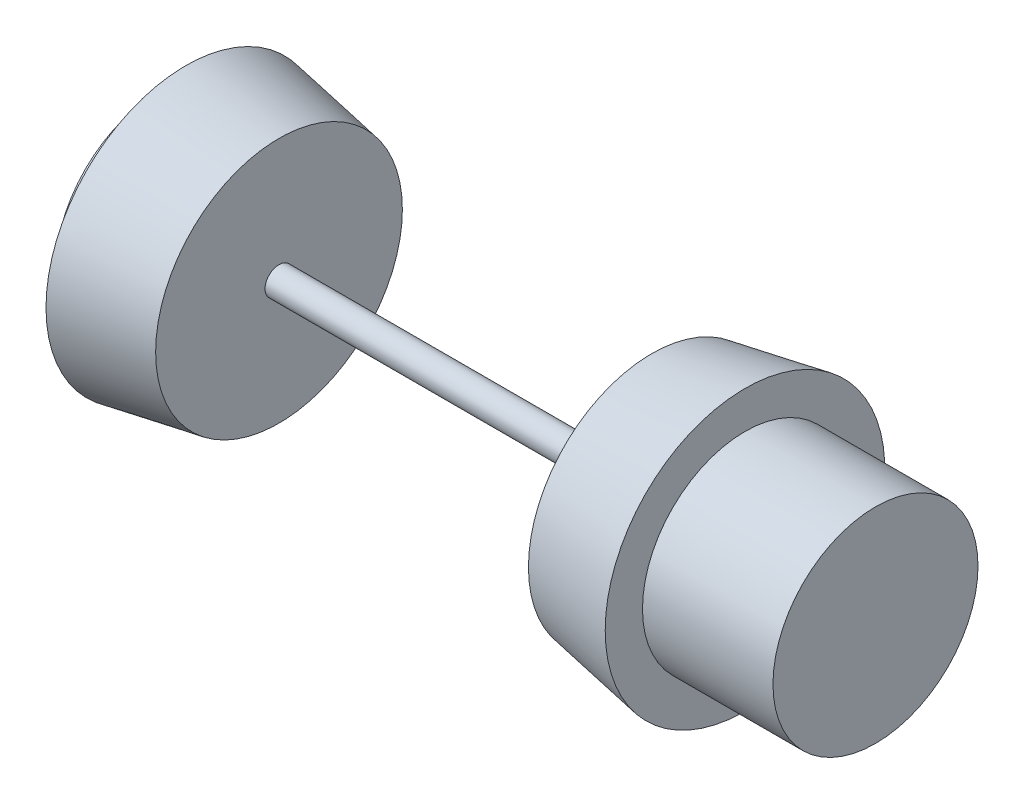
SolidWorks part; units mm, degrees
ref_plane "Front Plane" through (0, 0, 0) normal (0, 0, 1) x (1, 0, 0)
ref_plane "Top Plane" through (0, 0, 0) normal (0, 1, 0) x (1, 0, 0)
ref_plane "Right Plane" through (0, 0, 0) normal (1, 0, 0) x (0, 0, -1)
sketch "Sketch1" plane through (0, 0, 0) normal (1, 0, 0) x (0, 0, -1)
  circle A0 centre (0, 0) radius 1.5
  dimension "D1" = 3
extrude "Boss-Extrude1" add sketch "Sketch1" along normal blind 30
sketch "Sketch2" plane through (30, 0, 0) normal (1, 0, 0) x (0, 0, -1)
  circle A0 centre (0, 0) radius 11
  dimension "D1" = 22
extrude "Boss-Extrude2" add sketch "Sketch2" along normal blind 14
sketch "Sketch4" plane through (30, 0, 0) normal (-1, 0, 0) x (0, 0, 1)
  circle A0 centre (0, 0) radius 15
extrude "Boss-Extrude4" add sketch "Sketch4" along normal blind 10 draft 10
mirror "Mirror2" about plane through (0, 0, 0) normal (1, 0, 0) of "Boss-Extrude1", "Boss-Extrude4"
sketch "Sketch6" plane through (-30, 0, 0) normal (-1, 0, 0) x (0, 0, 1)
  circle A0 centre (0, 0) radius 11
  dimension "D1" = 22
extrude "Boss-Extrude5" add sketch "Sketch6" along normal blind 3
